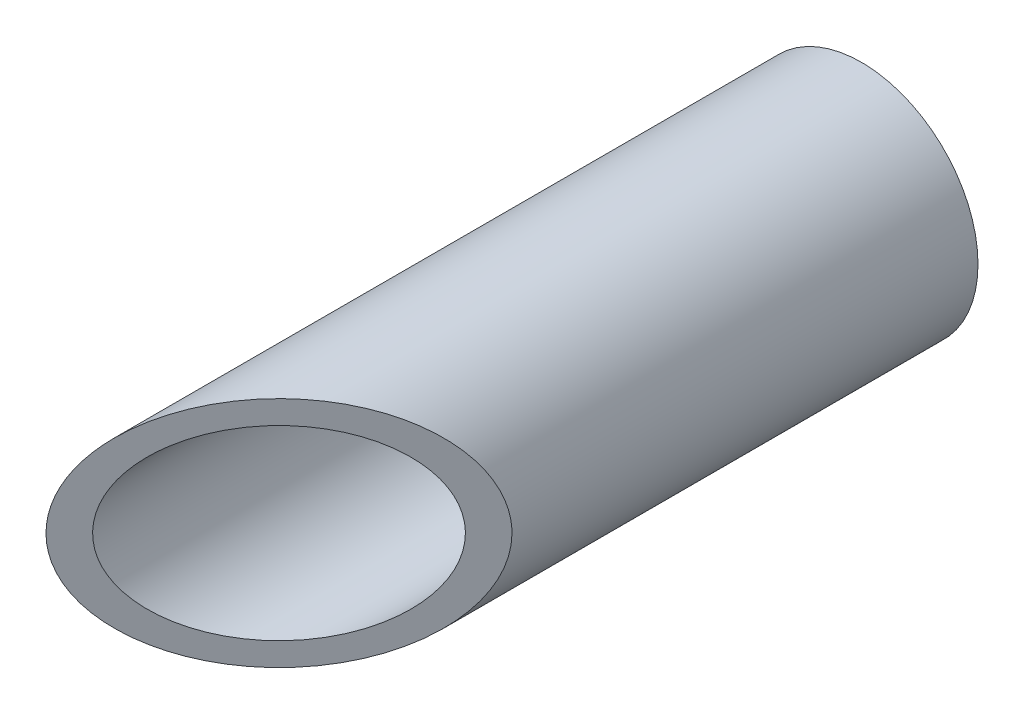
SolidWorks part; units mm, degrees
ref_plane "Front Plane" through (0, 0, 0) normal (0, 0, 1) x (1, 0, 0)
ref_plane "Top Plane" through (0, 0, 0) normal (0, 1, 0) x (1, 0, 0)
ref_plane "Right Plane" through (0, 0, 0) normal (1, 0, 0) x (0, 0, -1)
sketch "Sketch1" plane through (0, 0, 0) normal (0, 0, 1) x (1, 0, 0)
  circle A0 centre (0, 0) radius 25
  circle A1 centre (0, 0) radius 20
  dimension "D1" = 50
  dimension "D2" = 5
extrude "Boss-Extrude1" add sketch "Sketch1" along normal blind 150
ref_plane "Plane1" through (0, -25, 0) normal (0, -1, 0) x (-1, 0, 0)
sketch "Sketch2" plane through (0, -25, 0) normal (0, -1, 0) x (-1, 0, 0)
  line L0 (25, -150) -> (-25, -100)
  line L1 (-25, -150) -> (25, -150) construction
  line L2 (-25, 0) -> (-25, -150) construction
  line L3 (-25, -100) -> (-25, -150)
  line L4 (-25, -150) -> (25, -150)
  dimension "D1" = 50
  dimension "D2" = 50
extrude "Cut-Extrude1" cut sketch "Sketch2" against normal blind 500
